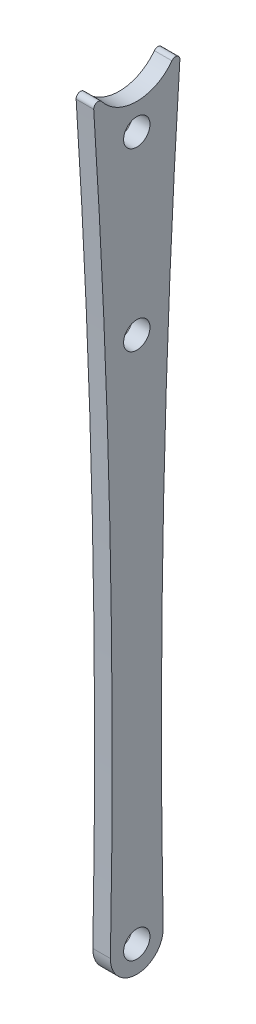
SolidWorks part; units mm, degrees
ref_plane "前视基准面" through (0, 0, 0) normal (0, 0, 1) x (1, 0, 0)
ref_plane "上视基准面" through (0, 0, 0) normal (0, 1, 0) x (1, 0, 0)
ref_plane "右视基准面" through (0, 0, 0) normal (1, 0, 0) x (0, 0, -1)
sketch "草图1" plane through (0, 0, 0) normal (1, 0, 0) x (0, 0, -1)
  line L0 (0, 0) -> (0, 49.3906) construction
  circle A0 centre (0, 0) radius 1.5
  arc A1 (-2.9994, 0.0596) -> (2.9994, 0.0596) centre (0, 0) ccw
  arc A2 (2.9994, 0.0596) -> (4.899, 84.6676) centre (1002.8018, 19.9383) cw
  arc A3 (4.899, 84.6676) -> (4, 85) centre (4.4, 84.7) ccw
  arc A4 (4, 85) -> (-4, 85) centre (0, 88) cw
  arc A5 (-4.899, 84.6676) -> (-4, 85) centre (-4.4, 84.7) cw
  arc A6 (-2.9994, 0.0596) -> (-4.899, 84.6676) centre (-1002.8018, 19.9383) ccw
  circle A7 centre (0, 80) radius 1.5
  circle A8 centre (0, 60) radius 1.5
  dimension "D1" = 1000
  dimension "D2" = 5
  dimension "D3" = 0.5
  dimension "D5" = 20
  dimension "D6" = 80
  dimension "D7" = 3
  dimension "D8" = 3
  dimension "D9" = 8
  dimension "D4" = 4
extrude "凸台-拉伸1" add sketch "草图1" along normal blind 2
move or copy body "实体-移动/复制1" [suppressed] bodies to move or copy 106
